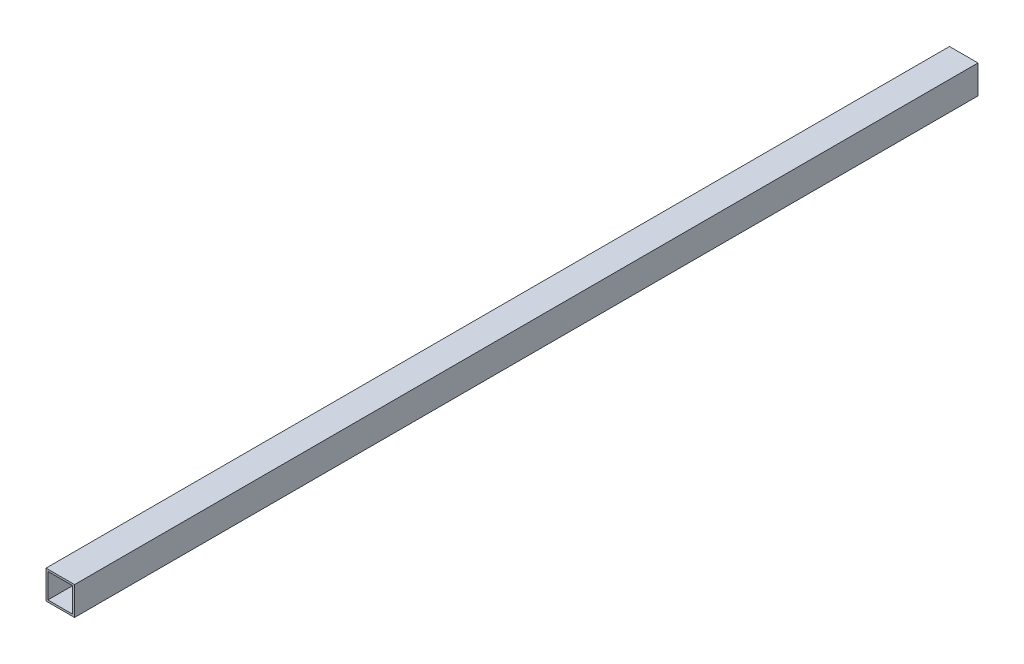
SolidWorks part; units mm, degrees
ref_plane "Alzado" through (0, 0, 0) normal (0, 0, 1) x (1, 0, 0)
ref_plane "Planta" through (0, 0, 0) normal (0, 1, 0) x (1, 0, 0)
ref_plane "Vista lateral" through (0, 0, 0) normal (1, 0, 0) x (0, 0, -1)
sketch "Croquis1" plane through (0, 0, 0) normal (0, 0, 1) x (1, 0, 0)
  line L1 (15, -15) -> (-15, -15)
  line L2 (15, -15) -> (15, 15)
  line L3 (15, 15) -> (-15, 15)
  line L4 (-15, -15) -> (-15, 15)
  line L5 (15, -15) -> (-15, 15) construction
  line L6 (15, 15) -> (-15, -15) construction
  point P0 (0, 0)
  dimension "D2" = 30
extrude "Extruir-Lámina1" add sketch "Croquis1" along normal blind 950 thin
